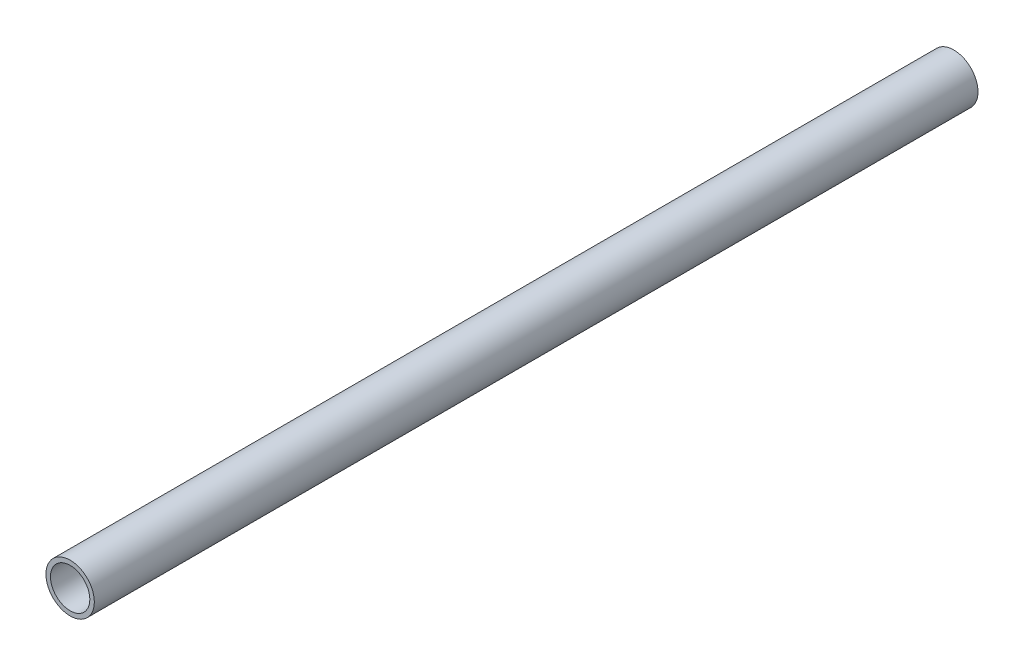
SolidWorks part; units mm, degrees
material "AISI 316 Annealed Stainless Steel Bar (SS)"
ref_plane "Front Plane" through (0, 0, 0) normal (0, 0, 1) x (1, 0, 0)
ref_plane "Top Plane" through (0, 0, 0) normal (0, 1, 0) x (1, 0, 0)
ref_plane "Right Plane" through (0, 0, 0) normal (1, 0, 0) x (0, 0, -1)
sketch "Sketch1" plane through (0, 0, 0) normal (0, 0, 1) x (1, 0, 0)
  circle A0 centre (0, 0) radius 4.7625
  circle A1 centre (0, 0) radius 3.8735
  dimension "D1" = 9.525
  dimension "D2" = 7.747
extrude "Boss-Extrude1" add sketch "Sketch1" along normal blind 174
